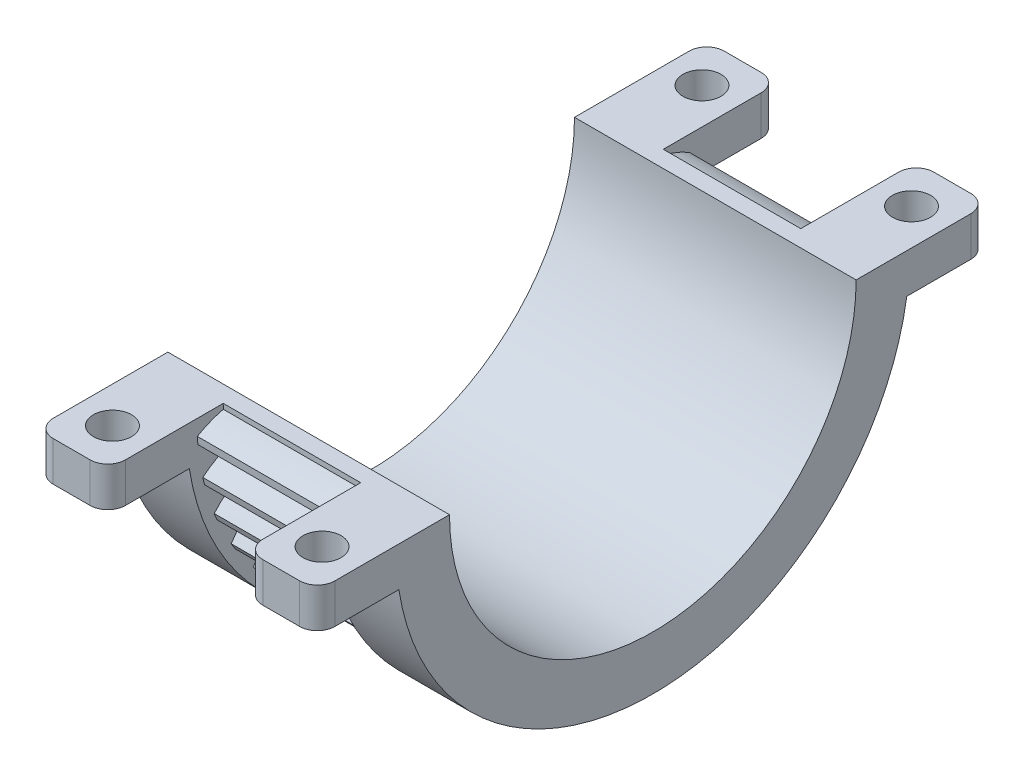
SolidWorks part; units mm, degrees
ref_plane "Plane1" through (0, 0, 0) normal (0, 0, 1) x (1, 0, 0)
ref_plane "Plane2" through (0, 0, 0) normal (0, 1, 0) x (1, 0, 0)
ref_plane "Plane3" through (0, 0, 0) normal (1, 0, 0) x (0, 0, -1)
sketch "HoldingSke" plane through (0, 0, 0) normal (0, 1, 0) x (1, 0, 0)
  line L0 (0, 0) -> (0.383, -0.3214)
  line L1 (-15, 0) -> (100, 0) construction
  line L2 (0, 0) -> (-2.1039, 2.3779)
  line L3 (0, 0) -> (-11.863, 4.5341)
  line L4 (0, 0) -> (6.6156, 5.5511)
  line L5 (0, 0) -> (-46.8476, -17.4728)
  line L6 (0, 0) -> (-39.7902, -26.8466)
  line L7 (-2.1039, 2.3779) -> (8.6586, 51.2059)
  line L8 (-76.2, 54.61) -> (-71.3, 54.61)
  line L9 (-71.009, 38.7566) -> (-53.1078, 45.2721)
  line L10 (-76.2, 71.12) -> (104.1128, 71.12)
  line L11 (0, 0) -> (-48, 0)
  line L12 (-76.2, 101.6) -> (-76.133, 101.6)
  line L13 (24.9733, 27.94) -> (52.9518, 28.4284)
  line L14 (24.9733, 27.94) -> (24.9743, 27.94)
  line L15 (24.9733, 27.94) -> (100.4006, 29.5858)
  line L16 (-63.627, -2) -> (-12.827, -2)
  circle A0 centre (0, 0) radius 32.5
  circle A1 centre (0, 0) radius 37.499
  circle A2 centre (0, 0) radius 37.5
  circle A3 centre (0, 0) radius 32.5
  dimension "MHD" = 74.998
  dimension "Hub_dia" = 75
  dimension "Bore" = 65
  dimension "MBD" = 65
  dimension "Num_teeth" = 40
  dimension "Pitch" = 0.5
  dimension "Overall_len" = 50
  dimension "Show_teeth" = 40
  dimension "Thickness" = 48
  dimension "OAL" = 50.0001
  dimension "T_dim" = 4.9
  dimension "Ap" = 20
  dimension "H" = 19.05
  dimension "Pitch_radius" = 180.3128
  dimension "Width" = 48
  dimension "Backlash" = 0.067
  dimension "Addendum_fac" = 1
  dimension "Dedendum_fac" = 1.25
  dimension "Clearance_fac" = 0.25
  dimension "Dedendum_add" = 0.001
  dimension "Module" = 2
sketch "BasProSke" plane through (0, 0, 0) normal (0, 1, 0) x (1, 0, 0)
  line L0 (-10, 0) -> (60, 0) construction
  line L1 (0, 0) -> (0, 42)
  line L2 (0, 0) -> (48, 0)
  line L3 (48, 0) -> (48, 42)
  line L4 (48, 42) -> (0, 42)
  dimension "Thickness" = 48
  dimension "Diameter" = 84
revolve "Base-Revolve" add sketch "BasProSke" angle 360 about L0
sketch "TooCutSke" plane through (0, 0, 0) normal (1, 0, 0) x (0, 0, -1)
  line L1 (0, 0) -> (0, 107) construction
  line L2 (0, 0) -> (-1.6876, 39.9644) construction
  line L3 (0, 0) -> (-6.2726, 79.7007) construction
  line L4 (-1.6876, 39.9644) -> (-3.1363, 39.8504) construction
  arc A0 (0.8828, 37.4886) -> (-0.8828, 37.4886) centre (0, 0) ccw
  arc A1 (2.6784, 41.94) -> (-2.6784, 41.94) centre (0, 0) ccw
  circle A2 centre (0, 0) radius 40 construction
  circle A3 centre (0, 0) radius 37.5877 construction
  arc A4 (-0.8828, 37.4886) -> (-2.6784, 41.94) centre (-16.451, 33.7965) ccw
  arc A5 (2.6784, 41.94) -> (0.8828, 37.4886) centre (16.451, 33.7965) ccw
  dimension "Root_dia" = 74.998
  dimension "Overcut_dia" = 84.0508
  dimension "Pitch_dia" = 80
  dimension "Base_dia" = 75.1754
  dimension "Flank_rad" = 16
  dimension "Half_ang" = 4.5
  dimension "Half_CT" = 1.4531
extrude "ToothCut" cut sketch "TooCutSke" along normal through all
fillet "Breaks" [suppressed] radius 0.04
fillet "RootFillets" [suppressed] radius 0.501
pattern_circular "TeethCuts" count 40 every 9 about axis through (-10, 0, 0) along (1, 0, 0) of "ToothCut", "RootFillets", "Breaks"
sketch "HubNeaOneSke" plane through (0, 0, 0) normal (-1, 0, 0) x (0, 0, 1)
  circle A0 centre (0, 0) radius 37.499
  dimension "Diameter" = 74.998
extrude "HubNearOne" [suppressed] add sketch "HubNeaOneSke" along normal blind 2.0001
sketch "HubNeaBotSke" plane through (0, 0, 0) normal (-1, 0, 0) x (0, 0, 1)
  circle A0 centre (0, 0) radius 37.499
  dimension "Diameter" = 74.998
extrude "HubNearBoth" [suppressed] add sketch "HubNeaBotSke" along normal blind 1
ref_plane "FarPln" through (48, 0, 0) normal (1, 0, 0) x (0, 0, -1)
sketch "HubFarSke" plane through (48, 0, 0) normal (1, 0, 0) x (0, 0, -1)
  circle A0 centre (0, 0) radius 37.499
  dimension "Diameter" = 74.998
extrude "HubFar" [suppressed] add sketch "HubFarSke" along normal blind 1
sketch "BorSke" plane through (0, 0, 0) normal (1, 0, 0) x (0, 0, -1)
  circle A0 centre (0, 0) radius 32.5
  dimension "Diameter" = 65
extrude "Bore" cut sketch "BorSke" along normal mid plane 100.0001
sketch "KeySke" plane through (0, 0, 0) normal (1, 0, 0) x (0, 0, -1)
  line L0 (-10, 0) -> (-10, 37.4)
  line L1 (-10, 37.4) -> (10, 37.4)
  line L2 (10, 37.4) -> (10, 0)
  line L3 (0, 0) -> (0, 34) construction
  line L4 (-10, 0) -> (10, 0)
  dimension "Offset" = 37.4
  dimension "Width" = 20
extrude "Keyway" [suppressed] cut sketch "KeySke" along normal mid plane 100.0001
pattern_circular "Keyway2" [suppressed] count 2 every 90 about axis through (-10, 0, 0) along (1, 0, 0)
sketch "Sketch1" plane through (0, 0, 0) normal (-1, 0, 0) x (0, 0, 1)
  circle A1 centre (0, 0) radius 34.5 construction
  circle A2 centre (0, 0) radius 34.65
  dimension "D1" = 69
  dimension "D2" = 0.15
extrude "Cut-Extrude1" cut sketch "Sketch1" against normal through all both and the other way through all
sketch "Sketch2" plane through (48, 0, 0) normal (1, 0, 0) x (0, 0, -1)
  line L0 (-51.2805, 0) -> (51.6171, 0) construction
  line L1 (-51.2805, -0.1) -> (51.6171, -0.1)
  line L3 (-51.2805, 0) -> (51.6171, 0)
  line L4 (-51.2805, 0) -> (-51.2805, 48.3771)
  line L5 (-51.2805, 48.3771) -> (51.6171, 48.3771)
  line L6 (51.6171, 0) -> (51.6171, 48.3771)
  dimension "D1" = 0.1
extrude "Cut-Extrude2" cut sketch "Sketch2" against normal through all both and the other way through all contours L3 L6 L5 L4
sketch "Sketch3" plane through (48, 0, 0) normal (1, 0, 0) x (0, 0, -1)
  line L0 (34.65, 0) -> (57.1826, 0)
  line L1 (43.2785, -6.7403) -> (57.1826, -6.7403)
  line L2 (-34.65, 0) -> (-57.1826, 0)
  line L5 (-57.1826, 0) -> (-57.1826, -6.7403)
  line L6 (-57.1826, -6.7403) -> (-43.2785, -6.7403)
  line L7 (57.1826, 0) -> (57.1826, -6.7403)
  arc A0 (-43.2785, -6.7403) -> (43.2785, -6.7403) centre (0, 0) ccw
  arc A1 (-34.65, 0) -> (34.65, 0) centre (0, 0) ccw construction
  arc A2 (-34.65, 0) -> (34.65, 0) centre (0, 0) ccw
extrude "Boss-Extrude1" add sketch "Sketch3" against normal blind 12.2882
ref_plane "Plane4" through (24, 0, 0) normal (1, 0, 0) x (0, 0, -1)
mirror "Mirror1" about plane through (24, 0, 0) normal (1, 0, 0) of "Boss-Extrude1"
sketch "Sketch4" plane through (0, -6.7403, 0) normal (0, -1, 0) x (1, 0, 0)
  line L0 (35.7118, 50.2305) -> (48, 50.2305) construction
  line L1 (35.7118, 57.1826) -> (35.7118, 43.2785) construction
  line L2 (48, 57.1826) -> (48, 43.2785) construction
  circle A0 centre (41.8559, 50.2305) radius 3.25
  dimension "D1" = 6.5
extrude "Cut-Extrude3" cut sketch "Sketch4" against normal through all both and the other way through all
ref_plane "Plane5" through (0, 0, 0) normal (0, 0, 1) x (1, 0, 0)
mirror "Mirror2" about plane through (0, 0, 0) normal (0, 0, 1) of "Cut-Extrude3"
mirror "Mirror3" about plane through (24, 0, 0) normal (1, 0, 0) of "Mirror2", "Cut-Extrude3"
fillet "Fillet1" radius 3 8 edges at (0, -3.3702, 57.1826) (12.2882, -3.3702, 57.1826) (48, -3.3702, 57.1826) (35.7118, -3.3702, 57.1826) (35.7118, -3.3702, -57.1826) (48, -3.3702, -57.1826) (0, -3.3702, -57.1826) (12.2882, -3.3702, -57.1826)
equation "' \"Module@HoldingSke\" = 6.35"
equation "' \"Num_teeth@HoldingSke\" = 12"
equation "' \"Ap@HoldingSke\" =  20"
equation "' \"Ap@HoldingSke\" = 20"
equation "' \"Width@HoldingSke\" = 0.5 * 25.4"
equation "' \"Hub_dia@HoldingSke\"= 1 * 25.4"
equation "' \"Hub_dia@HoldingSke\" = 1 * 25.4"
equation "' \"Overall_len@HoldingSke\" = 1.0 * 25.4"
equation "' \"Bore@HoldingSke\" = 0.75 * 25.4"
equation "' \"T_dim@HoldingSke\" = 0.1 * 25.4"
equation "' \"Width@KeySke\" = 0.25 * 25.4"
equation "' \"Show_teeth@HoldingSke\" = 13"
equation "' \"Backlash@HoldingSke\" = 0.009 * 25.4"
equation "' \"Addendum_fac@HoldingSke\" = 1.0"
equation "' \"Dedendum_fac@HoldingSke\" = 1.25"
equation "' \"Dedendum_add@HoldingSke\" = 0.00005 * 25.4"
equation "' \"Clearance_fac@HoldingSke\" = 0.25"
equation "\"Pitch@HoldingSke\" = 1 / \"Module@HoldingSke\""
equation "\"Overcut_dia@TooCutSke\" = (\"Num_teeth@HoldingSke\" + 2 * \"Addendum_fac@HoldingSke\") / \"Pitch@HoldingSke\" + 0.002 * 25.4"
equation "\"Pitch_dia@TooCutSke\" = \"Num_teeth@HoldingSke\" / \"Pitch@HoldingSke\""
equation "\"Base_dia@TooCutSke\" = \"Num_teeth@HoldingSke\" / \"Pitch@HoldingSke\" * cos((\"Ap@HoldingSke\"  * 3.14159265 / 180))"
equation "\"Root_dia@TooCutSke\" = (\"Num_teeth@HoldingSke\" + 2) / \"Pitch@HoldingSke\" - 2 * (\"Addendum_fac@HoldingSke\" + \"Dedendum_fac@HoldingSke\") / \"Pitch@HoldingSke\" - \"Dedendum_add@HoldingSke\" * 2"
equation "\"Half_ang@TooCutSke\" = 180 / \"Num_teeth@HoldingSke\""
equation "\"Half_CT@TooCutSke\" = \"Num_teeth@HoldingSke\" / \"Pitch@HoldingSke\" * sin((3.14159265 / 2 / \"Num_teeth@HoldingSke\")) / 2 - 7 * \"Backlash@HoldingSke\" / 4"
equation "\"Flank_rad@TooCutSke\" = \"Num_teeth@HoldingSke\" / \"Pitch@HoldingSke\" / 5"
equation "\"Radius@RootFillets\" = \"Clearance_fac@HoldingSke\" / \"Pitch@HoldingSke\" + \"Dedendum_add@HoldingSke\""
equation "\"Break_rad@Breaks\" = 0.02 / \"Pitch@HoldingSke\""
equation "\"Thickness@HoldingSke\" = \"Width@HoldingSke\""
equation "\"OAL@HoldingSke\" = \"Thickness@HoldingSke\""
equation "\"MHD@HoldingSke\" = (\"Num_teeth@HoldingSke\" + 2) / \"Pitch@HoldingSke\" - 2 * (\"Addendum_fac@HoldingSke\" + \"Dedendum_fac@HoldingSke\")  / \"Pitch@HoldingSke\" - \"Dedendum_add@HoldingSke\" * 2"
equation "\"MBD@HoldingSke\" = (\"Num_teeth@HoldingSke\" + 2) / \"Pitch@HoldingSke\" - 2 * (\"Addendum_fac@HoldingSke\" + \"Dedendum_fac@HoldingSke\")  / \"Pitch@HoldingSke\" - \"Dedendum_add@HoldingSke\" * 2 - 0.002 * 25.4"
equation "\"MHD@HoldingSke\" = ((sgn( \"MHD@HoldingSke\" - \"Hub_dia@HoldingSke\" )-1)*( \"MHD@HoldingSke\" - \"Hub_dia@HoldingSke\" ))/-2+ \"Hub_dia@HoldingSke\""
equation "\"MBD@HoldingSke\" = ((sgn( \"MBD@HoldingSke\" - \"Bore@HoldingSke\" )-1)*( \"MBD@HoldingSke\" - \"Bore@HoldingSke\" ))/-2+ \"Bore@HoldingSke\""
equation "\"OAL@HoldingSke\" = ((sgn( \"OAL@HoldingSke\" - \"Overall_len@HoldingSke\" )+1)*( \"OAL@HoldingSke\" - \"Overall_len@HoldingSke\" ))/2 + \"Overall_len@HoldingSke\" + 0.000002 * 25.4"
equation "\"Num_teeth@TeethCuts\" = int( \"Show_teeth@HoldingSke\" ) + 1"
equation "\"Num_teeth@TeethCuts\" = ((sgn( \"Num_teeth@TeethCuts\" - \"Num_teeth@HoldingSke\" )-1)*( \"Num_teeth@TeethCuts\" - \"Num_teeth@HoldingSke\" ))/-2+ \"Num_teeth@HoldingSke\""
equation "\"Num_teeth@TeethCuts\" = ((sgn( \"Num_teeth@TeethCuts\" - 2.0)+1)*( \"Num_teeth@TeethCuts\" - 2.0))/2 +2.0"
equation "\"Angle@TeethCuts\" = 360.0 / \"Num_teeth@HoldingSke\""
equation "\"Diameter@BasProSke\" = (\"Num_teeth@HoldingSke\" + 2 * \"Addendum_fac@HoldingSke\") / \"Pitch@HoldingSke\""
equation "\"Thickness@BasProSke\"  = \"Thickness@HoldingSke\""
equation "' \"Fillet_rad@BasProSke\" =  \"Thickness@HoldingSke\" * 0.05"
equation "' \"Fillet_rad@BasProSke\" = \"Thickness@HoldingSke\" * 0.05"
equation "\"MHD@HoldingSke\" = ((sgn( \"MHD@HoldingSke\" - \"Root_dia@TooCutSke\" )-1)*( \"MHD@HoldingSke\" - \"Root_dia@TooCutSke\" ))/-2+ \"Root_dia@TooCutSke\""
equation "\"Diameter@HubNeaOneSke\" = \"MHD@HoldingSke\""
equation "\"Length@HubNearOne\" = \"OAL@HoldingSke\" - \"Thickness@BasProSke\""
equation "\"Diameter@HubNeaBotSke\" = \"MHD@HoldingSke\""
equation "\"Length@HubNearBoth\" = ( \"OAL@HoldingSke\" - \"Thickness@BasProSke\" ) / 2.0"
equation "\"Thickness@FarPln\" = \"Thickness@BasProSke\""
equation "\"Diameter@HubFarSke\" = \"MHD@HoldingSke\""
equation "\"Length@HubFar\" = ( \"OAL@HoldingSke\" - \"Thickness@BasProSke\" ) / 2.0"
equation "\"Diameter@BorSke\" = \"MBD@HoldingSke\""
equation "\"D1@Bore\" = \"OAL@HoldingSke\" * 2.0"
equation "\"D1@Keyway\" = \"OAL@HoldingSke\" * 2.0"
equation "\"Offset@KeySke\" = \"T_dim@HoldingSke\" + \"MBD@HoldingSke\" / 2.0"
